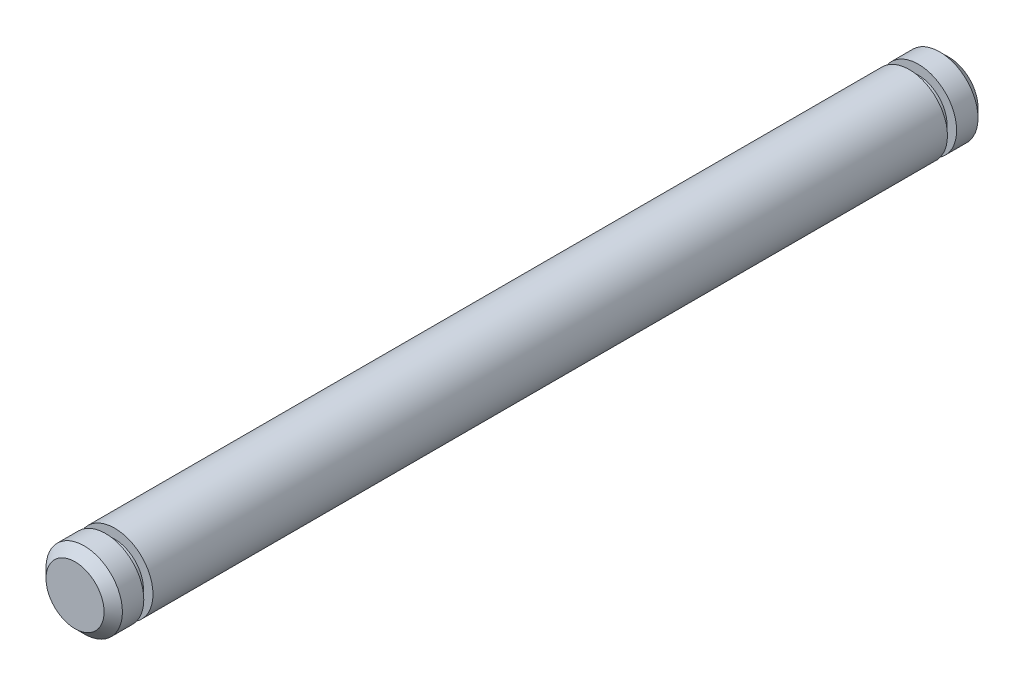
SolidWorks part; units mm, degrees
material "Alloy Steel"
ref_plane "Front Plane" through (0, 0, 0) normal (0, 0, 1) x (1, 0, 0)
ref_plane "Top Plane" through (0, 0, 0) normal (0, 1, 0) x (1, 0, 0)
ref_plane "Right Plane" through (0, 0, 0) normal (1, 0, 0) x (0, 0, -1)
sketch "Sketch1" plane through (0, 0, 0) normal (0, 0, 1) x (1, 0, 0)
  circle A0 centre (0, 0) radius 1.5875
  dimension "D1" = 3.175
extrude "Boss-Extrude1" add sketch "Sketch1" along normal mid plane 33.0149
sketch "Sketch2" plane through (0, 0, 16.5075) normal (0, 0, 1) x (1, 0, 0)
  circle A0 centre (0, 0) radius 1.1913
  dimension "D1" = 2.3825
extrude "Boss-Extrude2" add sketch "Sketch2" along normal blind 0.381
sketch "Sketch3" plane through (0, 0, 16.8885) normal (0, 0, 1) x (1, 0, 0)
  circle A0 centre (0, 0) radius 1.5875 construction
  circle A1 centre (0, 0) radius 1.5875
extrude "Boss-Extrude3" add sketch "Sketch3" along normal blind 1.27
chamfer "Chamfer1" distance 0.381 angle 45 1 edges at (1.5875, 0, 18.1585)
mirror "Mirror1" about plane through (0, 0, 0) normal (0, 0, 1) of "Boss-Extrude2", "Boss-Extrude3", "Chamfer1"
